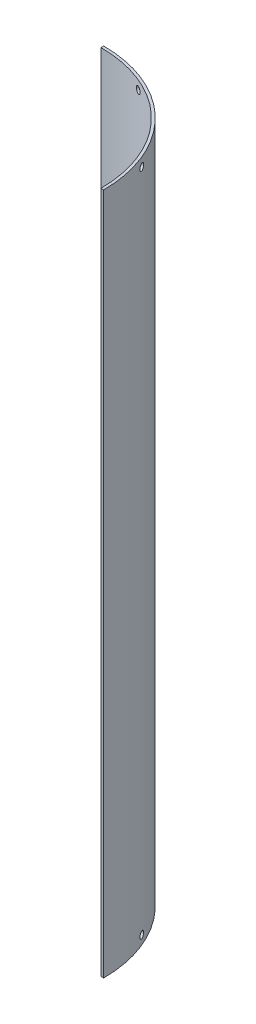
SolidWorks part; units mm, degrees
material "1060 Alloy"
ref_plane "Front Plane" through (0, 0, 0) normal (0, 0, 1) x (1, 0, 0)
ref_plane "Top Plane" through (0, 0, 0) normal (0, 1, 0) x (1, 0, 0)
ref_plane "Right Plane" through (0, 0, 0) normal (1, 0, 0) x (0, 0, -1)
sketch "Sketch1" plane through (0, 0, 0) normal (0, 1, 0) x (1, 0, 0)
  line L0 (0, 0) -> (0, 92)
  line L1 (0, 0) -> (92, 0)
  circle A0 centre (0, 0) radius 90
  circle A1 centre (0, 0) radius 92
  dimension "Internal Diameter" = 180
  dimension "External Diameter" = 184
extrude "Boss-Extrude1" add sketch "Sketch1" along normal blind 504 contours L1 A1 L0 A0
ref_plane "Plane1" through (0, 6.5, 0) normal (0, -1, 0) x (-1, 0, 0)
sketch "Sketch2" plane through (0, 6.5, 0) normal (0, -1, 0) x (-1, 0, 0)
  line L0 (0, 0) -> (-84.9969, 35.2069)
  line L1 (0, 0) -> (-65.0538, 65.0538)
  line L2 (0, 0) -> (-92, 0) construction
  line L3 (0, 0) -> (-35.2069, 84.9969)
  arc A0 (0, 92) -> (-92, 0) centre (0, 0) ccw construction
  dimension "D1" = 135
  dimension "D2" = 22.5
ref_plane "Plane2" through (84.9969, 0, -35.2069) normal (0.9239, 0, -0.3827) x (-0.3827, 0, -0.9239)
ref_plane "Plane3" through (35.2069, 0, -84.9969) normal (0.3827, 0, -0.9239) x (-0.9239, 0, -0.3827)
sketch "Sketch3" plane through (84.9969, 0, -35.2069) normal (0.9239, 0, -0.3827) x (-0.3827, 0, -0.9239)
  circle A0 centre (0, 6.5) radius 2.5
  point P0 (0, 6.5)
  dimension "Right Hole Diameter" = 5
sketch "Sketch5" plane through (35.2069, 0, -84.9969) normal (0.3827, 0, -0.9239) x (-0.9239, 0, -0.3827)
  line L0 (0, 6.5) -> (-84.9969, 6.5) construction
  circle A0 centre (0, 6.5) radius 2.5
  dimension "Left Hole Diameter" = 5
extrude "Cut-Extrude2" cut sketch "Sketch3" against normal up to surface (2.0347 mm away) contours A0
extrude "Cut-Extrude3" cut sketch "Sketch5" against normal up to surface (2.0347 mm away) contours A0
pattern_linear "LPattern2" count 2 spacing 491 along (0, 1, 0) of "Cut-Extrude2", "Cut-Extrude3"
move or copy body "Body-Move/Copy1" bodies to move or copy 109 copy no rotation origin (0, 252, 0) rotation axis (0.7071, 0, -0.7071) rotation angle 180
equation "\"Total Panel Length\"= 504"
equation "\"Internal Panel Diameter\"= 180"
equation "\"External Panel Diameter\"= 184"
equation "\"L & R Mounting Hole Diameter\"= 5"
equation "\"Mounting Hole Dist. from Top\"= 6.5"
equation "\"Mounting Hole Dist. from Base\"= 6.5"
equation "\"External Diameter@Sketch1\"= \"External Panel Diameter\""
equation "\"Internal Diameter@Sketch1\"= \"Internal Panel Diameter\""
equation "\"Panel Length@Boss-Extrude1\"= \"Total Panel Length\""
equation "\"Right Hole Diameter@Sketch3\"= \"L & R Mounting Hole Diameter\""
equation "\"Left Hole Diameter@Sketch5\"= \"L & R Mounting Hole Diameter\""
equation "\"Mounting from Top@Plane1\"= \"Mounting Hole Dist. from Top\""
equation "\"Mounting from Base@LPattern2\"= \"Total Panel Length\" - \"Mounting Hole Dist. from Base\" - \"Mounting Hole Dist. from Top\""
equation "\"Top Tab Length\"= 13"
equation "\"Base Tab Length\"= 13"
